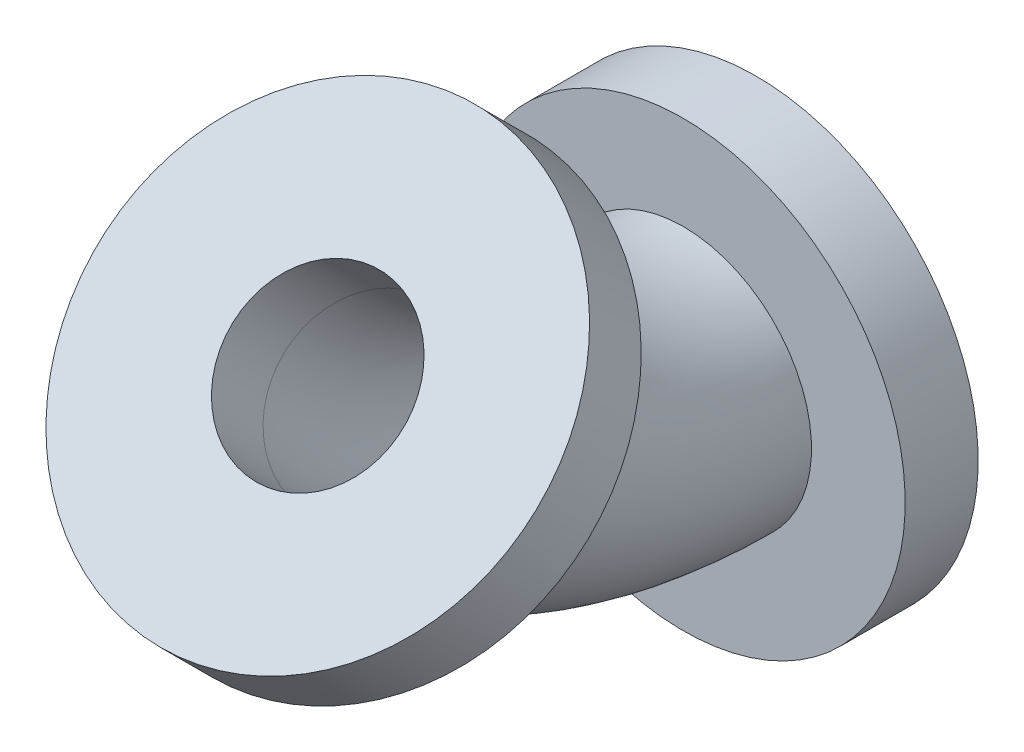
SolidWorks part; units mm, degrees
ref_plane "Plan de face" through (0, 0, 0) normal (0, 0, 1) x (1, 0, 0)
ref_plane "Plan de dessus" through (0, 0, 0) normal (0, 1, 0) x (1, 0, 0)
ref_plane "Plan de droite" through (0, 0, 0) normal (1, 0, 0) x (0, 0, -1)
sketch "Esquisse1" plane through (0, 0, 0) normal (1, 0, 0) x (0, 0, -1)
  line L0 (0, 0) -> (-47, 0)
  line L1 (-206.099, 65.901) -> (-232.262, 92.0639)
  line L2 (-206.099, 65.901) -> (-96.6007, 175.3993) construction
  line L3 (-47, 0) -> (-47, 156.175) construction
  arc A0 (-47, 0) -> (-206.099, 65.901) centre (-47, 225) cw
  dimension "D4" = 225
  dimension "D1" = 47
  dimension "D2" = 37
  dimension "D3" = 45
sketch "Esquisse2" plane through (0, 0, 0) normal (0, 0, 1) x (1, 0, 0)
  circle A0 centre (0, 0) radius 65
  dimension "D1" = 130
sweep "Balayage-Mince1" add profiles "Esquisse2" path "Esquisse1" parameters "D1"=21
sketch "Esquisse3" plane through (0, 0, 0) normal (0, 0, -1) x (-1, 0, 0)
  circle A0 centre (0, 0) radius 112.5
  circle A1 centre (0, 0) radius 44
  dimension "D1" = 225
extrude "Boss.-Extru.1" add sketch "Esquisse3" against normal blind 47
sketch "Esquisse4" plane through (0, 0, 0) normal (0, 0, -1) x (-1, 0, 0)
  circle A0 centre (0, 0) radius 65
  circle A1 centre (0, 0) radius 112.5
  dimension "D1" = 130
extrude "Enlèv. mat.-Extru.1" cut sketch "Esquisse4" against normal blind 10
sketch "Esquisse5" plane through (0, 162.163, 162.163) normal (0, 0.7071, 0.7071) x (1, 0, 0)
  circle A0 centre (0, -99.135) radius 112.5
  circle A1 centre (0, -99.135) radius 44
  dimension "D1" = 225
extrude "Boss.-Extru.2" add sketch "Esquisse5" against normal blind 37
